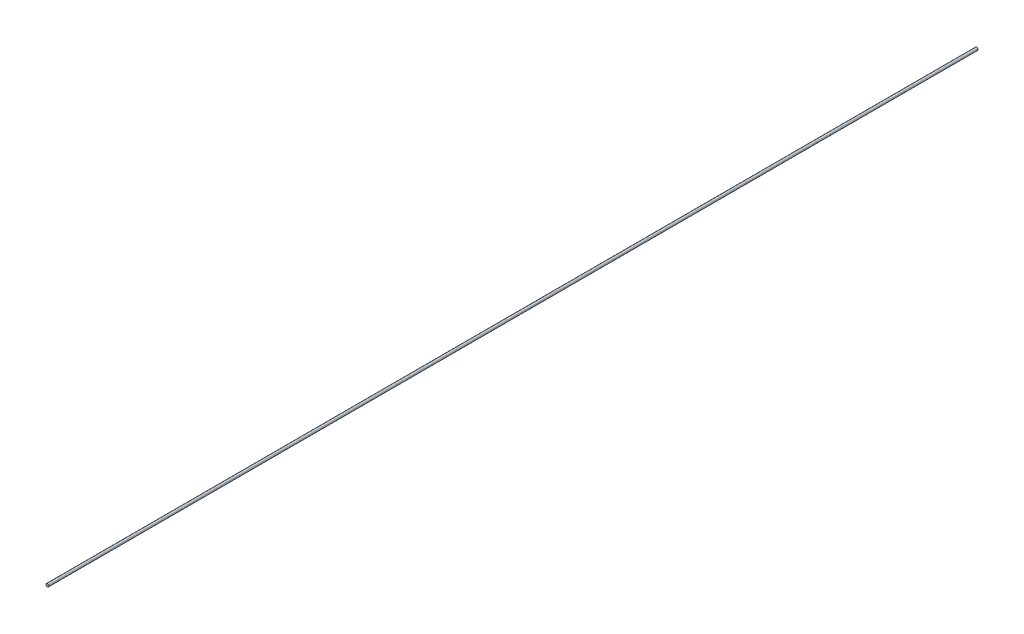
SolidWorks part; units mm, degrees
material "2014-O"
ref_plane "Front Plane" through (0, 0, 0) normal (0, 0, 1) x (1, 0, 0)
ref_plane "Top Plane" through (0, 0, 0) normal (0, 1, 0) x (1, 0, 0)
ref_plane "Right Plane" through (0, 0, 0) normal (1, 0, 0) x (0, 0, -1)
sketch "Sketch1" plane through (0, 0, 0) normal (0, 0, 1) x (1, 0, 0)
  circle A0 centre (0, 0) radius 25.4
  dimension "D1" = 50.8
extrude "Boss-Extrude1" add sketch "Sketch1" along normal blind 16757.2552
equation "\"diam\" = 2'diameter of bar[in]"
equation "\"D1@Sketch1\"=\"diam\""
equation "\"E\"= 10500000'Youngs M Al[psi]"
equation "\"del\"= 0.009'max deflection[in]"
equation "\"F\" = 450'Load[lbf]"
equation "\"A\"= \"diam\" * \"diam\" * pi / 4'X-sect area[in^2]"
equation "\"L\"= \"E\" * \"A\" * \"del\" / \"F\"'bar length[in]"
equation "\"D1@Boss-Extrude1\"=\"L\""
